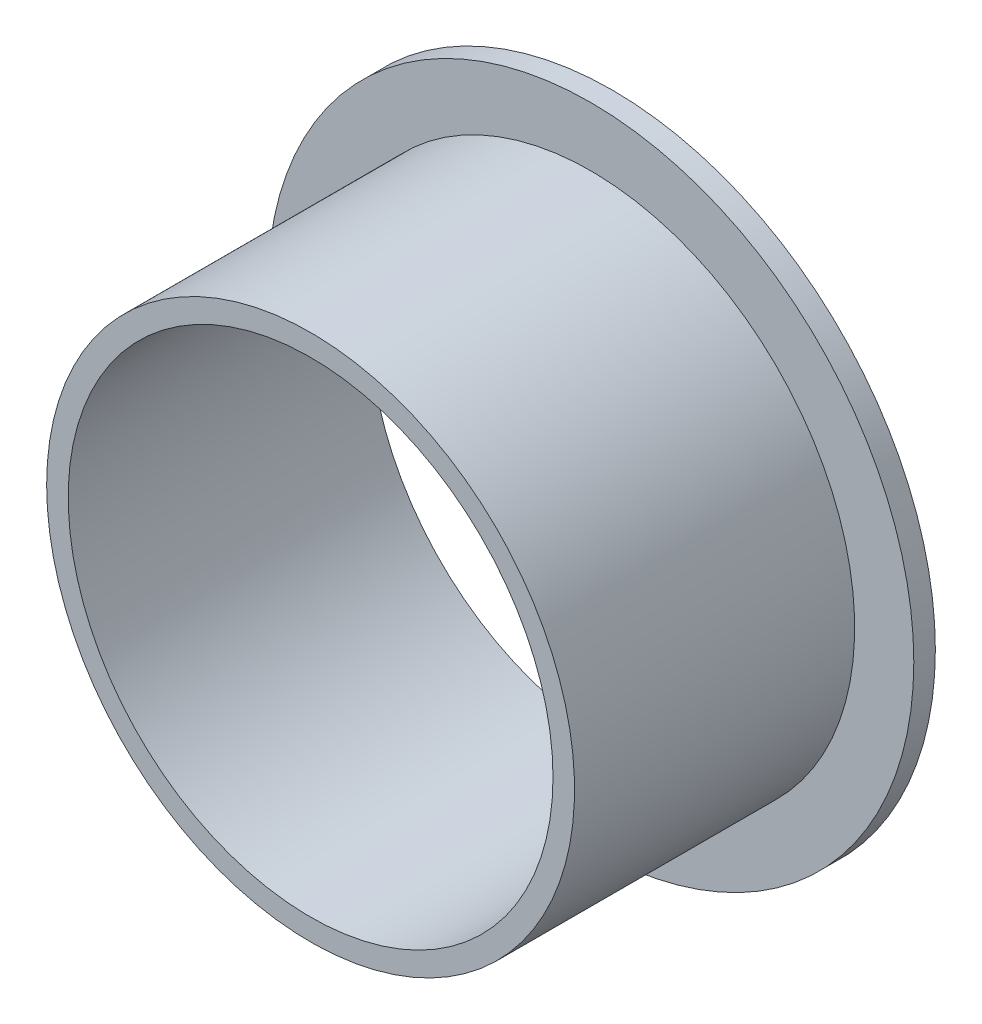
SolidWorks part; units mm, degrees
ref_plane "Front Plane" through (0, 0, 0) normal (0, 0, 1) x (1, 0, 0)
ref_plane "Top Plane" through (0, 0, 0) normal (0, 1, 0) x (1, 0, 0)
ref_plane "Right Plane" through (0, 0, 0) normal (1, 0, 0) x (0, 0, -1)
sketch "Sketch1" plane through (0, 0, 0) normal (0, 0, 1) x (1, 0, 0)
  circle A0 centre (0, 0) radius 45
  circle A1 centre (0, 0) radius 59.9797
  dimension "D1" = 90
  dimension "D2" = 119.9594
extrude "Boss-Extrude1" add sketch "Sketch1" along normal blind 4
sketch "Sketch2" plane through (0, 0, 4) normal (0, 0, 1) x (1, 0, 0)
  circle A0 centre (0, 0) radius 49
  circle A1 centre (0, 0) radius 45
  dimension "D1" = 90
  dimension "D2" = 98
extrude "Boss-Extrude2" add sketch "Sketch2" along normal blind 52
